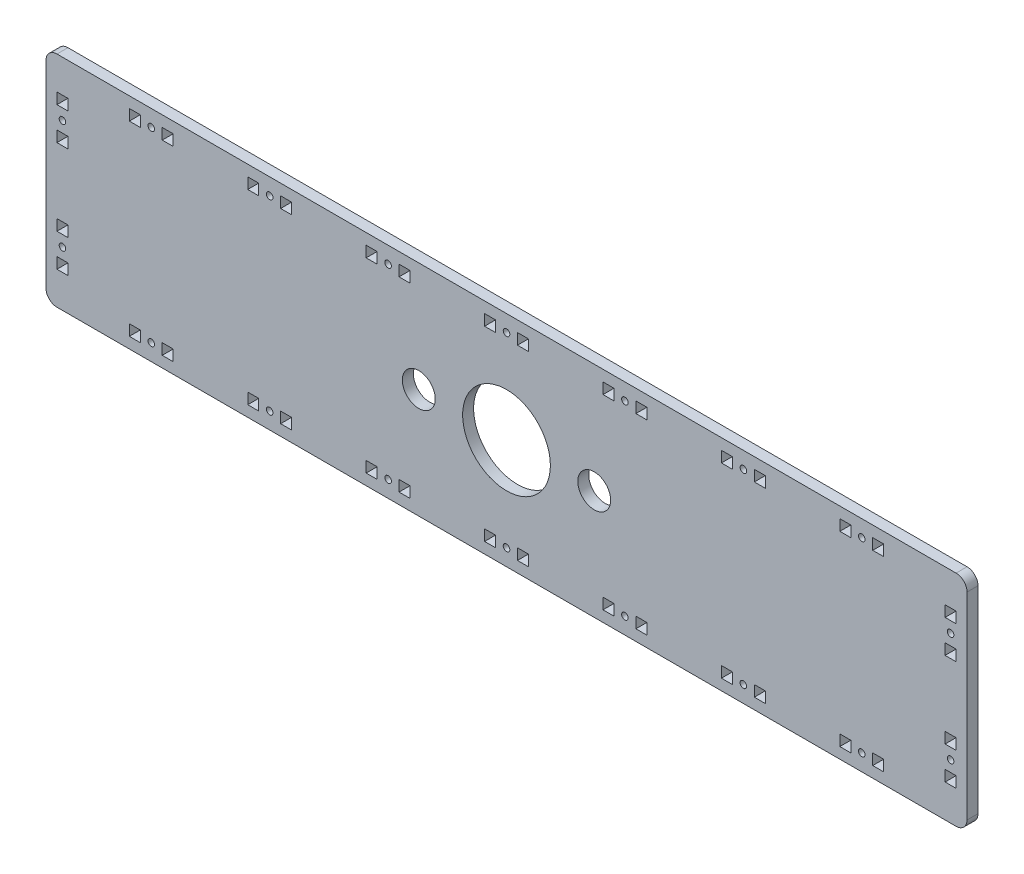
SolidWorks part; units mm, degrees
ref_plane "Front Plane" through (0, 0, 0) normal (0, 0, 1) x (1, 0, 0)
ref_plane "Top Plane" through (0, 0, 0) normal (0, 1, 0) x (1, 0, 0)
ref_plane "Right Plane" through (0, 0, 0) normal (1, 0, 0) x (0, 0, -1)
sketch "Sketch1" plane through (0, 0, 0) normal (0, 0, 1) x (1, 0, 0)
  line L0 (0, 40) -> (0, -40) construction
  line L1 (200, -40) -> (-200, -40) construction
  line L2 (200, -40) -> (200, 40) construction
  line L3 (200, 40) -> (-200, 40) construction
  line L4 (-200, -40) -> (-200, 40) construction
  line L5 (200, -40) -> (-200, 40) construction
  line L6 (200, 40) -> (-200, -40) construction
  line L7 (0, 0) -> (-102.5879, 0) construction
  line L9 (-210, -50) -> (210, -50)
  line L10 (-210, -50) -> (-210, 50)
  line L11 (-210, 50) -> (210, 50)
  line L12 (210, -50) -> (210, 50)
  line L13 (-210, -50) -> (210, 50) construction
  line L14 (-210, 50) -> (210, -50) construction
  circle A0 centre (0, 0) radius 20
  circle A1 centre (-40, 0) radius 7.5
  circle A2 centre (40, 0) radius 7.5
  point P0 (0, 0)
  line B0 (-5, -40) -> (-10, -40)
  line B1 (-5, -40) -> (-5, -45)
  line B2 (-5, -45) -> (-10, -45)
  line B3 (-10, -40) -> (-10, -45)
  line B4 (5, -40) -> (10, -40)
  line B5 (5, -40) -> (5, -45)
  line B6 (5, -45) -> (10, -45)
  line B7 (10, -40) -> (10, -45)
  circle B8 centre (0, -42.5) radius 1.5
  line B9 (-59, -40) -> (-64, -40)
  line B10 (-59, -40) -> (-59, -45)
  line B11 (-59, -45) -> (-64, -45)
  line B12 (-64, -40) -> (-64, -45)
  line B13 (-49, -40) -> (-44, -40)
  line B14 (-49, -40) -> (-49, -45)
  line B15 (-49, -45) -> (-44, -45)
  line B16 (-44, -40) -> (-44, -45)
  circle B17 centre (-54, -42.5) radius 1.5
  line B18 (-113, -40) -> (-118, -40)
  line B19 (-113, -40) -> (-113, -45)
  line B20 (-113, -45) -> (-118, -45)
  line B21 (-118, -40) -> (-118, -45)
  line B22 (-103, -40) -> (-98, -40)
  line B23 (-103, -40) -> (-103, -45)
  line B24 (-103, -45) -> (-98, -45)
  line B25 (-98, -40) -> (-98, -45)
  circle B26 centre (-108, -42.5) radius 1.5
  line B27 (-167, -40) -> (-172, -40)
  line B28 (-167, -40) -> (-167, -45)
  line B29 (-167, -45) -> (-172, -45)
  line B30 (-172, -40) -> (-172, -45)
  line B31 (-157, -40) -> (-152, -40)
  line B32 (-157, -40) -> (-157, -45)
  line B33 (-157, -45) -> (-152, -45)
  line B34 (-152, -40) -> (-152, -45)
  circle B35 centre (-162, -42.5) radius 1.5
  line B36 (-205, 20) -> (-205, 15)
  line B37 (-205, 20) -> (-200, 20)
  line B38 (-200, 20) -> (-200, 15)
  line B39 (-205, 15) -> (-200, 15)
  line B40 (-205, 30) -> (-205, 35)
  line B41 (-205, 30) -> (-200, 30)
  line B42 (-200, 30) -> (-200, 35)
  line B43 (-205, 35) -> (-200, 35)
  circle B44 centre (-202.5, 25) radius 1.5
  line B45 (59, -40) -> (64, -40)
  line B46 (59, -40) -> (59, -45)
  line B47 (59, -45) -> (64, -45)
  line B48 (64, -40) -> (64, -45)
  line B49 (49, -40) -> (44, -40)
  line B50 (49, -40) -> (49, -45)
  line B51 (49, -45) -> (44, -45)
  line B52 (44, -40) -> (44, -45)
  circle B53 centre (54, -42.5) radius 1.5
  line B54 (113, -40) -> (118, -40)
  line B55 (113, -40) -> (113, -45)
  line B56 (113, -45) -> (118, -45)
  line B57 (118, -40) -> (118, -45)
  line B58 (103, -40) -> (98, -40)
  line B59 (103, -40) -> (103, -45)
  line B60 (103, -45) -> (98, -45)
  line B61 (98, -40) -> (98, -45)
  circle B62 centre (108, -42.5) radius 1.5
  line B63 (167, -40) -> (172, -40)
  line B64 (167, -40) -> (167, -45)
  line B65 (167, -45) -> (172, -45)
  line B66 (172, -40) -> (172, -45)
  line B67 (157, -40) -> (152, -40)
  line B68 (157, -40) -> (157, -45)
  line B69 (157, -45) -> (152, -45)
  line B70 (152, -40) -> (152, -45)
  circle B71 centre (162, -42.5) radius 1.5
  line B72 (-59, 40) -> (-64, 40)
  line B73 (-59, 40) -> (-59, 45)
  line B74 (-59, 45) -> (-64, 45)
  line B75 (-64, 40) -> (-64, 45)
  line B76 (-49, 40) -> (-44, 40)
  line B77 (-49, 40) -> (-49, 45)
  line B78 (-49, 45) -> (-44, 45)
  line B79 (-44, 40) -> (-44, 45)
  circle B80 centre (-54, 42.5) radius 1.5
  line B81 (167, 40) -> (172, 40)
  line B82 (167, 40) -> (167, 45)
  line B83 (167, 45) -> (172, 45)
  line B84 (172, 40) -> (172, 45)
  line B85 (157, 40) -> (152, 40)
  line B86 (157, 40) -> (157, 45)
  line B87 (157, 45) -> (152, 45)
  line B88 (152, 40) -> (152, 45)
  circle B89 centre (162, 42.5) radius 1.5
  line B90 (-113, 40) -> (-118, 40)
  line B91 (-113, 40) -> (-113, 45)
  line B92 (-113, 45) -> (-118, 45)
  line B93 (-118, 40) -> (-118, 45)
  line B94 (-103, 40) -> (-98, 40)
  line B95 (-103, 40) -> (-103, 45)
  line B96 (-103, 45) -> (-98, 45)
  line B97 (-98, 40) -> (-98, 45)
  circle B98 centre (-108, 42.5) radius 1.5
  line B99 (-5, 40) -> (-10, 40)
  line B100 (-5, 40) -> (-5, 45)
  line B101 (-5, 45) -> (-10, 45)
  line B102 (-10, 40) -> (-10, 45)
  line B103 (5, 40) -> (10, 40)
  line B104 (5, 40) -> (5, 45)
  line B105 (5, 45) -> (10, 45)
  line B106 (10, 40) -> (10, 45)
  circle B107 centre (0, 42.5) radius 1.5
  line B108 (-167, 40) -> (-172, 40)
  line B109 (-167, 40) -> (-167, 45)
  line B110 (-167, 45) -> (-172, 45)
  line B111 (-172, 40) -> (-172, 45)
  line B112 (-157, 40) -> (-152, 40)
  line B113 (-157, 40) -> (-157, 45)
  line B114 (-157, 45) -> (-152, 45)
  line B115 (-152, 40) -> (-152, 45)
  circle B116 centre (-162, 42.5) radius 1.5
  line B117 (59, 40) -> (64, 40)
  line B118 (59, 40) -> (59, 45)
  line B119 (59, 45) -> (64, 45)
  line B120 (64, 40) -> (64, 45)
  line B121 (49, 40) -> (44, 40)
  line B122 (49, 40) -> (49, 45)
  line B123 (49, 45) -> (44, 45)
  line B124 (44, 40) -> (44, 45)
  circle B125 centre (54, 42.5) radius 1.5
  line B126 (113, 40) -> (118, 40)
  line B127 (113, 40) -> (113, 45)
  line B128 (113, 45) -> (118, 45)
  line B129 (118, 40) -> (118, 45)
  line B130 (103, 40) -> (98, 40)
  line B131 (103, 40) -> (103, 45)
  line B132 (103, 45) -> (98, 45)
  line B133 (98, 40) -> (98, 45)
  circle B134 centre (108, 42.5) radius 1.5
  line B135 (-205, -20) -> (-205, -15)
  line B136 (-205, -20) -> (-200, -20)
  line B137 (-200, -20) -> (-200, -15)
  line B138 (-205, -15) -> (-200, -15)
  line B139 (-205, -30) -> (-205, -35)
  line B140 (-205, -30) -> (-200, -30)
  line B141 (-200, -30) -> (-200, -35)
  line B142 (-205, -35) -> (-200, -35)
  circle B143 centre (-202.5, -25) radius 1.5
  line B144 (205, 20) -> (205, 15)
  line B145 (205, 20) -> (200, 20)
  line B146 (200, 20) -> (200, 15)
  line B147 (205, 15) -> (200, 15)
  line B148 (205, 30) -> (205, 35)
  line B149 (205, 30) -> (200, 30)
  line B150 (200, 30) -> (200, 35)
  line B151 (205, 35) -> (200, 35)
  circle B152 centre (202.5, 25) radius 1.5
  line B153 (205, -20) -> (205, -15)
  line B154 (205, -20) -> (200, -20)
  line B155 (200, -20) -> (200, -15)
  line B156 (205, -15) -> (200, -15)
  line B157 (205, -30) -> (205, -35)
  line B158 (205, -30) -> (200, -30)
  line B159 (200, -30) -> (200, -35)
  line B160 (205, -35) -> (200, -35)
  circle B161 centre (202.5, -25) radius 1.5
  dimension "D9" = 15
  dimension "D11" = 40
  dimension "D1" = 400
  dimension "D2" = 80
  dimension "D3" = 54
  dimension "D4" = 54
  dimension "D5" = 54
  dimension "D6" = 25
  dimension "D7" = 100
  dimension "D8" = 420
  dimension "D10" = 40
sketch_block_instance "Trou M3 plots 5mm-1"
sketch_block "Trou M3 plots 5mm" parameters "D2"=3, "D1"=5, "D3"=5, "D4"=10
sketch_block_instance "Trou M3 plots 5mm-2"
sketch_block_instance "Trou M3 plots 5mm-3"
sketch_block_instance "Trou M3 plots 5mm-4"
sketch_block_instance "Trou M3 plots 5mm-9"
sketch_block_instance "Trou M3 plots 5mm-13"
sketch_block_instance "Trou M3 plots 5mm-14"
sketch_block_instance "Trou M3 plots 5mm-15"
sketch_block_instance "Trou M3 plots 5mm-16"
sketch_block_instance "Trou M3 plots 5mm-17"
sketch_block_instance "Trou M3 plots 5mm-18"
sketch_block_instance "Trou M3 plots 5mm-19"
sketch_block_instance "Trou M3 plots 5mm-20"
sketch_block_instance "Trou M3 plots 5mm-21"
sketch_block_instance "Trou M3 plots 5mm-22"
sketch_block_instance "Trou M3 plots 5mm-23"
sketch_block_instance "Trou M3 plots 5mm-24"
sketch_block_instance "Trou M3 plots 5mm-25"
extrude "Boss-Extrude1" add sketch "Sketch1" along normal blind 5
fillet "Fillet1" radius 5 4 edges at (210, -50, 2.5) (210, 50, 2.5) (-210, -50, 2.5) (-210, 50, 2.5)
